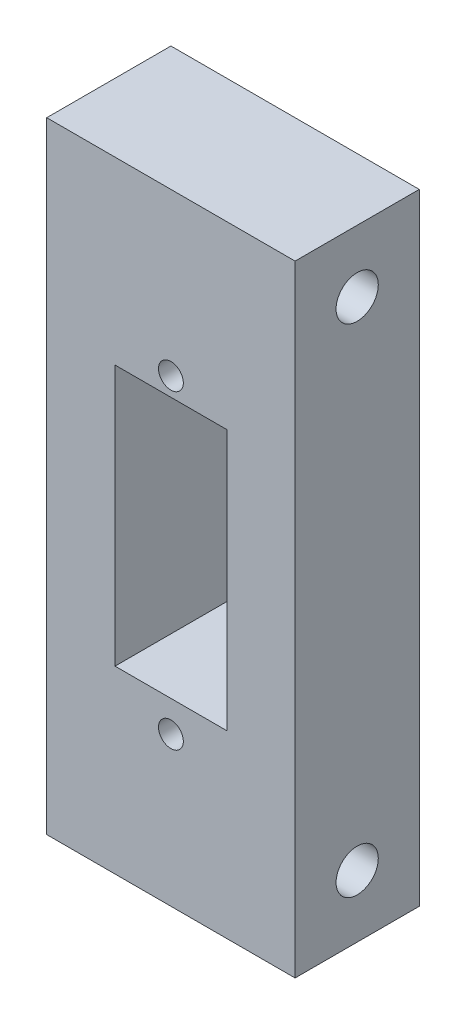
SolidWorks part; units mm, degrees
ref_plane "前视基准面" through (0, 0, 0) normal (0, 0, 1) x (1, 0, 0)
ref_plane "上视基准面" through (0, 0, 0) normal (0, 1, 0) x (1, 0, 0)
ref_plane "右视基准面" through (0, 0, 0) normal (1, 0, 0) x (0, 0, -1)
sketch "草图3" plane through (0, 0, 0) normal (0, 0, 1) x (1, 0, 0)
  line L1 (4.5, -10.5) -> (-4.5, -10.5)
  line L2 (4.5, -10.5) -> (4.5, 10.5)
  line L3 (4.5, 10.5) -> (-4.5, 10.5)
  line L4 (-4.5, -10.5) -> (-4.5, 10.5)
  line L5 (4.5, -10.5) -> (-4.5, 10.5) construction
  line L6 (4.5, 10.5) -> (-4.5, -10.5) construction
  line L7 (10, 25) -> (-10, 25)
  line L8 (10, 25) -> (10, -25)
  line L9 (10, -25) -> (-10, -25)
  line L10 (-10, 25) -> (-10, -25)
  line L11 (10, 25) -> (-10, -25) construction
  line L12 (10, -25) -> (-10, 25) construction
  circle A0 centre (0, -13) radius 1
  circle A1 centre (0, 12) radius 1
  point P0 (0, 0)
  point P6 (0, 0)
  point P15 (0, 0)
extrude "凸台-拉伸1" add sketch "草图3" along normal blind 10
sketch "草图4" plane through (10, 0, 0) normal (1, 0, 0) x (0, 0, -1)
  line L0 (-5, -25) -> (-5, 25) construction
  line L1 (-10, -25) -> (0, -25) construction
  line L2 (-10, 25) -> (0, 25) construction
  circle A0 centre (-5, -20) radius 1.7
  circle A1 centre (-5, 20) radius 1.7
extrude "切除-拉伸1" cut sketch "草图4" against normal through all
